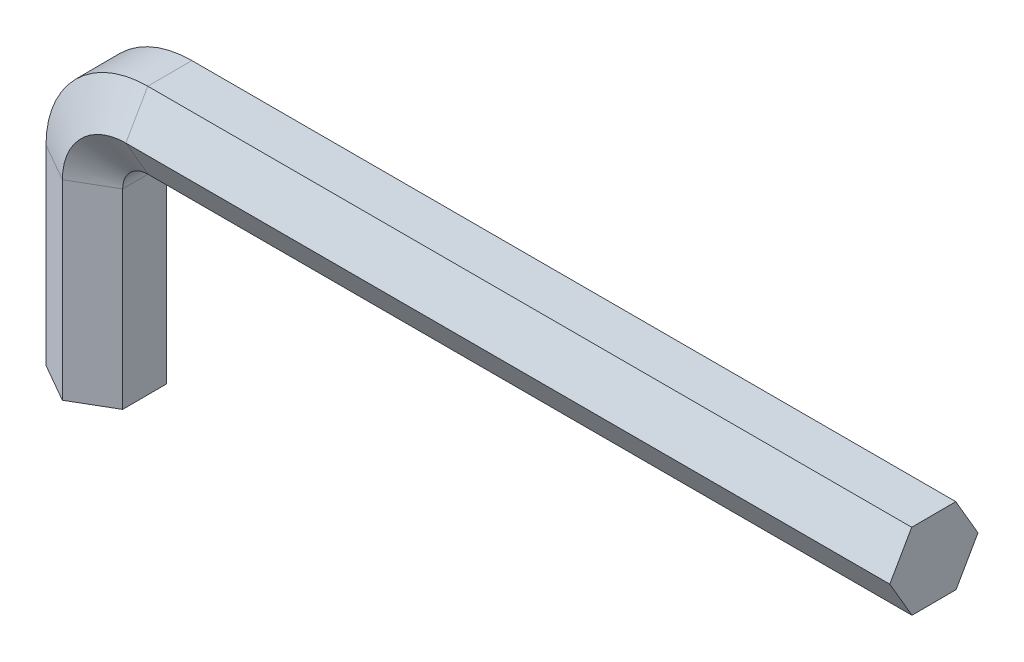
SolidWorks part; units mm, degrees
ref_plane "Front Plane" through (0, 0, 0) normal (0, 0, 1) x (1, 0, 0)
ref_plane "Top Plane" through (0, 0, 0) normal (0, 1, 0) x (1, 0, 0)
ref_plane "Right Plane" through (0, 0, 0) normal (1, 0, 0) x (0, 0, -1)
sketch "Sketch1" plane through (0, 0, 0) normal (0, 0, 1) x (1, 0, 0)
  line L0 (0, 0) -> (-60, 0)
  line L1 (-65, -5) -> (-65, -20)
  arc A0 (-60, 0) -> (-65, -5) centre (-60, -5) ccw
  dimension "D1" = 5
ref_plane "Plane1" through (0, 0, 0) normal (-1, 0, 0) x (0, 0, 1)
sketch "Sketch2" plane through (0, 0, 0) normal (-1, 0, 0) x (0, 0, 1)
  line L1 (1.7208, -3.0065) -> (3.4641, -0.013)
  line L2 (3.4641, -0.013) -> (1.7433, 2.9935)
  line L3 (1.7433, 2.9935) -> (-1.7208, 3.0065)
  line L4 (-1.7208, 3.0065) -> (-3.4641, 0.013)
  line L5 (-3.4641, 0.013) -> (-1.7433, -2.9935)
  line L6 (-1.7433, -2.9935) -> (1.7208, -3.0065)
  circle A0 centre (0, 0) radius 3 construction
sweep "Sweep1" add profiles "Sketch2" path "Sketch1"
